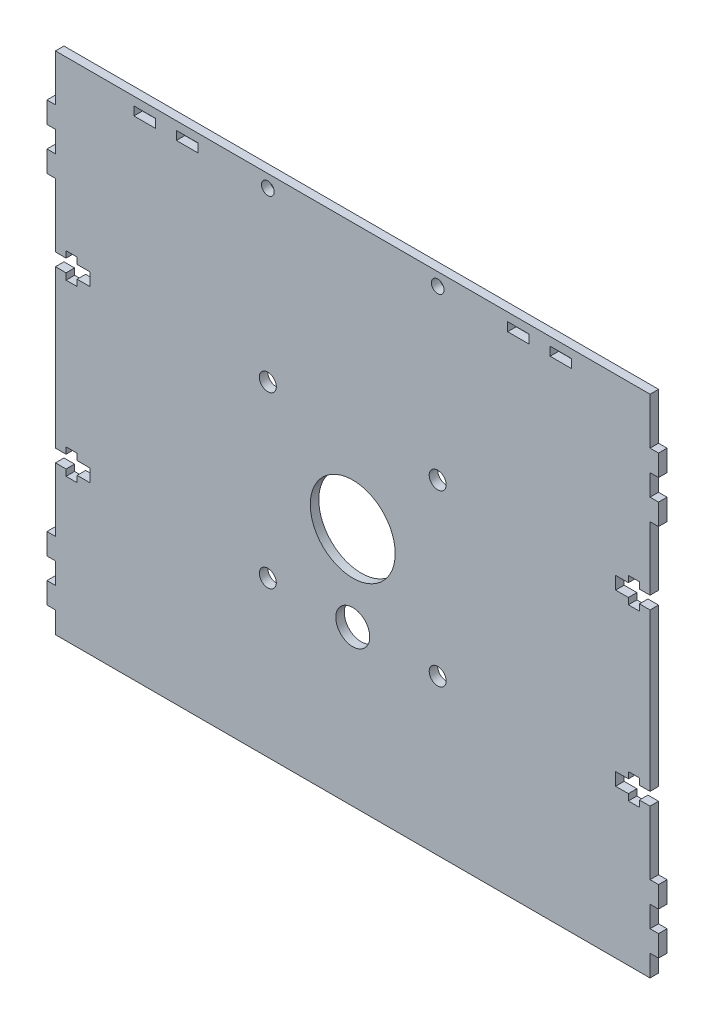
SolidWorks part; units mm, degrees
ref_plane "前视基准面" through (0, 0, 0) normal (0, 0, 1) x (1, 0, 0)
ref_plane "上视基准面" through (0, 0, 0) normal (0, 1, 0) x (1, 0, 0)
ref_plane "右视基准面" through (0, 0, 0) normal (1, 0, 0) x (0, 0, -1)
sketch "草图1" plane through (0, 0, 0) normal (0, 0, 1) x (1, 0, 0)
  line L50 (249.9534, 275.9629) -> (249.9534, 255.9629) construction
  line L53 (317.4534, 257.4629) -> (317.4534, 258.9629)
  line L54 (317.4534, 254.4629) -> (317.4534, 252.9629)
  line L55 (319.9534, 254.4629) -> (317.4534, 254.4629)
  line L56 (317.4534, 258.9629) -> (314.8534, 258.9629)
  line L57 (314.8534, 258.9629) -> (314.8534, 257.4629)
  line L58 (314.8534, 257.4629) -> (311.8534, 257.4629)
  line L59 (311.8534, 254.4629) -> (311.8534, 257.4629)
  line L60 (314.8534, 254.4629) -> (311.8534, 254.4629)
  line L61 (314.8534, 252.9629) -> (314.8534, 254.4629)
  line L62 (317.4534, 252.9629) -> (314.8534, 252.9629)
  line L63 (317.4534, 257.4629) -> (319.9534, 257.4629)
  line L68 (319.9534, 254.4629) -> (319.9534, 257.4629) construction
  line L69 (311.8534, 255.9629) -> (319.9534, 255.9629) construction
  line L73 (311.8534, 295.9629) -> (319.9534, 295.9629) construction
  line L75 (317.4534, 294.4629) -> (319.9534, 294.4629)
  line L76 (317.4534, 298.9629) -> (314.8534, 298.9629)
  line L77 (314.8534, 298.9629) -> (314.8534, 297.4629)
  line L78 (314.8534, 297.4629) -> (311.8534, 297.4629)
  line L79 (311.8534, 297.4629) -> (311.8534, 294.4629)
  line L80 (314.8534, 294.4629) -> (311.8534, 294.4629)
  line L81 (314.8534, 292.9629) -> (314.8534, 294.4629)
  line L82 (317.4534, 292.9629) -> (314.8534, 292.9629)
  line L83 (319.9534, 297.4629) -> (317.4534, 297.4629)
  line L84 (317.4534, 297.4629) -> (317.4534, 298.9629)
  line L85 (317.4534, 294.4629) -> (317.4534, 292.9629)
  line L111 (182.4534, 294.4629) -> (182.4534, 292.9629)
  line L112 (182.4534, 297.4629) -> (182.4534, 298.9629)
  line L113 (179.9534, 297.4629) -> (182.4534, 297.4629)
  line L114 (182.4534, 292.9629) -> (185.0534, 292.9629)
  line L115 (185.0534, 292.9629) -> (185.0534, 294.4629)
  line L116 (185.0534, 294.4629) -> (188.0534, 294.4629)
  line L117 (188.0534, 297.4629) -> (188.0534, 294.4629)
  line L118 (185.0534, 297.4629) -> (188.0534, 297.4629)
  line L119 (185.0534, 298.9629) -> (185.0534, 297.4629)
  line L120 (182.4534, 298.9629) -> (185.0534, 298.9629)
  line L121 (182.4534, 294.4629) -> (179.9534, 294.4629)
  line L122 (182.4534, 257.4629) -> (179.9534, 257.4629)
  line L123 (182.4534, 252.9629) -> (185.0534, 252.9629)
  line L124 (185.0534, 252.9629) -> (185.0534, 254.4629)
  line L125 (185.0534, 254.4629) -> (188.0534, 254.4629)
  line L126 (188.0534, 254.4629) -> (188.0534, 257.4629)
  line L127 (185.0534, 257.4629) -> (188.0534, 257.4629)
  line L128 (185.0534, 258.9629) -> (185.0534, 257.4629)
  line L129 (182.4534, 258.9629) -> (185.0534, 258.9629)
  line L130 (179.9534, 254.4629) -> (182.4534, 254.4629)
  line L131 (182.4534, 254.4629) -> (182.4534, 252.9629)
  line L132 (182.4534, 257.4629) -> (182.4534, 258.9629)
  line L133 (179.9534, 297.4629) -> (179.9534, 294.4629) construction
  line L134 (188.0534, 295.9629) -> (179.9534, 295.9629) construction
  line L135 (188.0534, 255.9629) -> (179.9534, 255.9629) construction
  line L163 (179.9534, 294.4629) -> (179.9534, 257.4629)
  line L172 (319.9534, 257.4629) -> (319.9534, 294.4629)
  line L188 (179.9534, 239.4629) -> (177.9534, 239.4629)
  line L189 (177.9534, 239.4629) -> (177.9534, 234.4629)
  line L190 (177.9534, 234.4629) -> (179.9534, 234.4629)
  line L191 (179.9534, 234.4629) -> (179.9534, 229.4629)
  line L192 (179.9534, 229.4629) -> (177.9534, 229.4629)
  line L193 (177.9534, 229.4629) -> (177.9534, 224.4629)
  line L194 (177.9534, 224.4629) -> (179.9534, 224.4629)
  line L196 (179.9534, 327.4629) -> (179.9534, 345.9629) construction
  line L197 (177.9534, 327.4629) -> (179.9534, 327.4629)
  line L198 (177.9534, 322.4629) -> (177.9534, 327.4629)
  line L199 (179.9534, 322.4629) -> (177.9534, 322.4629)
  line L200 (179.9534, 317.4629) -> (179.9534, 322.4629)
  line L201 (177.9534, 317.4629) -> (179.9534, 317.4629)
  line L202 (177.9534, 312.4629) -> (177.9534, 317.4629)
  line L203 (179.9534, 312.4629) -> (177.9534, 312.4629)
  line L224 (319.9534, 312.4629) -> (321.9534, 312.4629)
  line L225 (321.9534, 312.4629) -> (321.9534, 317.4629)
  line L226 (321.9534, 317.4629) -> (319.9534, 317.4629)
  line L227 (319.9534, 317.4629) -> (319.9534, 322.4629)
  line L228 (319.9534, 322.4629) -> (321.9534, 322.4629)
  line L229 (321.9534, 322.4629) -> (321.9534, 327.4629)
  line L230 (321.9534, 327.4629) -> (319.9534, 327.4629)
  line L231 (319.9534, 327.4629) -> (319.9534, 345.9629) construction
  line L233 (321.9534, 224.4629) -> (319.9534, 224.4629)
  line L234 (321.9534, 229.4629) -> (321.9534, 224.4629)
  line L235 (319.9534, 229.4629) -> (321.9534, 229.4629)
  line L236 (319.9534, 234.4629) -> (319.9534, 229.4629)
  line L237 (321.9534, 234.4629) -> (319.9534, 234.4629)
  line L238 (321.9534, 239.4629) -> (321.9534, 234.4629)
  line L239 (319.9534, 239.4629) -> (321.9534, 239.4629)
  line L261 (249.9534, 255.9629) -> (229.9534, 255.9629) construction
  line L262 (229.9534, 335.4629) -> (269.9534, 335.4629) construction
  line L263 (249.9534, 335.4629) -> (249.9534, 338.4629) construction
  line L268 (179.9534, 297.4629) -> (179.9534, 312.4629)
  line L271 (319.9534, 312.4629) -> (319.9534, 297.4629)
  line L272 (319.9534, 254.4629) -> (319.9534, 239.4629)
  line L275 (179.9534, 239.4629) -> (179.9534, 254.4629)
  line L279 (319.9534, 338.4629) -> (179.9534, 338.4629)
  line L280 (179.9534, 327.4629) -> (179.9534, 338.4629)
  line L285 (319.9534, 338.4629) -> (319.9534, 327.4629)
  line L286 (319.9534, 219.4131) -> (179.9534, 219.4131) construction
  line L287 (319.9534, 219.4131) -> (319.9534, 224.4629)
  line L288 (179.9534, 224.4629) -> (179.9534, 219.4131)
  line L289 (319.9534, 219.4131) -> (179.9534, 219.4131)
  line L309 (179.9534, 345.9629) -> (319.9534, 345.9629) construction
  line L310 (203.4784, 334.4379) -> (198.4284, 336.4879) construction
  line L311 (286.4284, 336.4879) -> (291.4784, 336.4879)
  line L312 (286.4284, 336.4879) -> (286.4284, 334.4379)
  line L313 (286.4284, 334.4379) -> (291.4784, 334.4379)
  line L314 (291.4784, 336.4879) -> (291.4784, 334.4379)
  line L315 (286.4284, 336.4879) -> (291.4784, 334.4379) construction
  line L316 (286.4284, 334.4379) -> (291.4784, 336.4879) construction
  line L317 (296.4284, 336.4879) -> (301.4784, 336.4879)
  line L318 (296.4284, 336.4879) -> (296.4284, 334.4379)
  line L319 (296.4284, 334.4379) -> (301.4784, 334.4379)
  line L320 (301.4784, 336.4879) -> (301.4784, 334.4379)
  line L321 (296.4284, 336.4879) -> (301.4784, 334.4379) construction
  line L322 (296.4284, 334.4379) -> (301.4784, 336.4879) construction
  line L323 (268.4534, 343.4629) -> (266.9534, 343.4629) [skipped]
  line L324 (271.4534, 343.4629) -> (272.9534, 343.4629) [skipped]
  line L325 (271.4534, 345.9629) -> (271.4534, 343.4629) [skipped]
  line L326 (266.9534, 343.4629) -> (266.9534, 340.8629) [skipped]
  line L327 (266.9534, 340.8629) -> (268.4534, 340.8629) [skipped]
  line L328 (268.4534, 340.8629) -> (268.4534, 337.8629) [skipped]
  line L329 (271.4534, 340.8629) -> (271.4534, 337.8629) [skipped]
  line L330 (272.9534, 340.8629) -> (271.4534, 340.8629) [skipped]
  line L331 (272.9534, 343.4629) -> (272.9534, 340.8629) [skipped]
  line L332 (268.4534, 343.4629) -> (268.4534, 345.9629) [skipped]
  line L333 (231.4534, 343.4629) -> (231.4534, 345.9629) [skipped]
  line L334 (226.9534, 343.4629) -> (226.9534, 340.8629) [skipped]
  line L335 (226.9534, 340.8629) -> (228.4534, 340.8629) [skipped]
  line L336 (228.4534, 340.8629) -> (228.4534, 337.8629) [skipped]
  line L337 (231.4534, 340.8629) -> (231.4534, 337.8629) [skipped]
  line L338 (232.9534, 340.8629) -> (231.4534, 340.8629) [skipped]
  line L339 (232.9534, 343.4629) -> (232.9534, 340.8629) [skipped]
  line L340 (228.4534, 345.9629) -> (228.4534, 343.4629) [skipped]
  line L341 (228.4534, 343.4629) -> (226.9534, 343.4629) [skipped]
  line L342 (231.4534, 343.4629) -> (232.9534, 343.4629) [skipped]
  line L343 (268.4534, 345.9629) -> (231.4534, 345.9629) [skipped]
  line L344 (213.4534, 345.9629) -> (213.4534, 347.9629) [skipped]
  line L345 (213.4534, 347.9629) -> (208.4534, 347.9629) [skipped]
  line L346 (208.4534, 347.9629) -> (208.4534, 345.9629) [skipped]
  line L347 (208.4534, 345.9629) -> (203.4534, 345.9629) [skipped]
  line L348 (203.4534, 345.9629) -> (203.4534, 347.9629) [skipped]
  line L349 (203.4534, 347.9629) -> (198.4534, 347.9629) [skipped]
  line L350 (198.4534, 347.9629) -> (198.4534, 345.9629) [skipped]
  line L352 (301.4534, 345.9629) -> (319.9534, 345.9629) [skipped]
  line L353 (301.4534, 347.9629) -> (301.4534, 345.9629) [skipped]
  line L354 (296.4534, 347.9629) -> (301.4534, 347.9629) [skipped]
  line L355 (296.4534, 345.9629) -> (296.4534, 347.9629) [skipped]
  line L356 (291.4534, 345.9629) -> (296.4534, 345.9629) [skipped]
  line L357 (291.4534, 347.9629) -> (291.4534, 345.9629) [skipped]
  line L358 (286.4534, 347.9629) -> (291.4534, 347.9629) [skipped]
  line L359 (286.4534, 345.9629) -> (286.4534, 347.9629) [skipped]
  line L360 (271.4534, 345.9629) -> (268.4534, 345.9629) construction
  line L361 (269.9534, 337.8629) -> (269.9534, 345.9629) construction
  line L362 (229.9534, 337.8629) -> (229.9534, 345.9629) construction
  line L363 (271.4534, 337.8629) -> (268.4534, 337.8629) [skipped]
  line L364 (228.4534, 337.8629) -> (231.4534, 337.8629) [skipped]
  line L365 (203.4784, 336.4879) -> (198.4284, 334.4379) construction
  line L366 (213.4784, 334.4379) -> (208.4284, 336.4879) construction
  line L367 (213.4784, 336.4879) -> (208.4284, 334.4379) construction
  line L368 (198.4284, 336.4879) -> (198.4284, 334.4379)
  line L369 (203.4784, 334.4379) -> (198.4284, 334.4379)
  line L370 (203.4784, 336.4879) -> (203.4784, 334.4379)
  line L371 (203.4784, 336.4879) -> (198.4284, 336.4879)
  line L372 (208.4284, 336.4879) -> (208.4284, 334.4379)
  line L373 (213.4784, 334.4379) -> (208.4284, 334.4379)
  line L374 (213.4784, 336.4879) -> (213.4784, 334.4379)
  line L375 (213.4784, 336.4879) -> (208.4284, 336.4879)
  line L376 (231.4534, 208.4629) -> (232.9534, 208.4629) [skipped]
  line L377 (228.4534, 208.4629) -> (226.9534, 208.4629) [skipped]
  line L378 (228.4534, 205.9629) -> (228.4534, 208.4629) [skipped]
  line L379 (232.9534, 208.4629) -> (232.9534, 211.0629) [skipped]
  line L380 (232.9534, 211.0629) -> (231.4534, 211.0629) [skipped]
  line L381 (231.4534, 211.0629) -> (231.4534, 214.0629) [skipped]
  line L382 (228.4534, 214.0629) -> (231.4534, 214.0629) [skipped]
  line L383 (228.4534, 211.0629) -> (228.4534, 214.0629) [skipped]
  line L384 (226.9534, 211.0629) -> (228.4534, 211.0629) [skipped]
  line L385 (226.9534, 208.4629) -> (226.9534, 211.0629) [skipped]
  line L386 (231.4534, 208.4629) -> (231.4534, 205.9629) [skipped]
  line L387 (268.4534, 208.4629) -> (268.4534, 205.9629) [skipped]
  line L388 (272.9534, 208.4629) -> (272.9534, 211.0629) [skipped]
  line L389 (272.9534, 211.0629) -> (271.4534, 211.0629) [skipped]
  line L390 (271.4534, 211.0629) -> (271.4534, 214.0629) [skipped]
  line L391 (271.4534, 214.0629) -> (268.4534, 214.0629) [skipped]
  line L392 (268.4534, 211.0629) -> (268.4534, 214.0629) [skipped]
  line L393 (266.9534, 211.0629) -> (268.4534, 211.0629) [skipped]
  line L394 (266.9534, 208.4629) -> (266.9534, 211.0629) [skipped]
  line L395 (271.4534, 205.9629) -> (271.4534, 208.4629) [skipped]
  line L396 (271.4534, 208.4629) -> (272.9534, 208.4629) [skipped]
  line L397 (268.4534, 208.4629) -> (266.9534, 208.4629) [skipped]
  line L398 (231.4534, 205.9629) -> (268.4534, 205.9629) [skipped]
  line L399 (286.4534, 205.9629) -> (286.4534, 203.9629) [skipped]
  line L400 (286.4534, 203.9629) -> (291.4534, 203.9629) [skipped]
  line L401 (291.4534, 203.9629) -> (291.4534, 205.9629) [skipped]
  line L402 (291.4534, 205.9629) -> (296.4534, 205.9629) [skipped]
  line L403 (296.4534, 205.9629) -> (296.4534, 203.9629) [skipped]
  line L404 (296.4534, 203.9629) -> (301.4534, 203.9629) [skipped]
  line L405 (198.4534, 205.9629) -> (179.9534, 205.9629) [skipped]
  line L406 (198.4534, 203.9629) -> (198.4534, 205.9629) [skipped]
  line L407 (203.4534, 203.9629) -> (198.4534, 203.9629) [skipped]
  line L408 (203.4534, 205.9629) -> (203.4534, 203.9629) [skipped]
  line L409 (208.4534, 205.9629) -> (203.4534, 205.9629) [skipped]
  line L410 (208.4534, 203.9629) -> (208.4534, 205.9629) [skipped]
  line L411 (213.4534, 203.9629) -> (208.4534, 203.9629) [skipped]
  line L412 (213.4534, 205.9629) -> (213.4534, 203.9629) [skipped]
  line L413 (228.4534, 205.9629) -> (231.4534, 205.9629) construction
  line L414 (229.9534, 214.0629) -> (229.9534, 205.9629) construction
  line L415 (269.9534, 214.0629) -> (269.9534, 205.9629) construction
  line L416 (319.9534, 224.4629) -> (319.9534, 205.9629) [skipped]
  line L417 (301.4534, 203.9629) -> (301.4534, 205.9629) [skipped]
  circle A14 centre (249.9534, 275.9629) radius 10
  circle A24 centre (249.9534, 255.9629) radius 4
  circle A27 centre (229.9534, 335.4629) radius 1.5
  circle A28 centre (269.9534, 335.4629) radius 1.5
  circle A29 centre (229.9534, 255.9629) radius 2
  circle A30 centre (229.9534, 295.9629) radius 2
  circle A31 centre (269.9534, 295.9629) radius 2
  circle A32 centre (269.9534, 255.9629) radius 2
  circle A33 centre (249.9534, 255.9629) radius 31.5 construction
  point P107 (210.9534, 335.4629)
  point P232 (288.9534, 335.4629)
  dimension "D1" = 140
  dimension "D5" = 4
  dimension "D4" = 4
extrude "凸台-拉伸1" add sketch "草图1" along normal blind 2
sketch "草图2" plane through (179.9534, 0, 0) normal (-1, 0, 0) x (0, 0, 1)
  line L0 (1, 294.4629) -> (1, 297.4629) construction
  line L1 (2, 294.4629) -> (0, 294.4629) construction
  line L2 (2, 297.4629) -> (0, 297.4629) construction
  line L3 (1, 295.9629) -> (1, 312.4629) construction
  line L4 (2, 312.4629) -> (0, 312.4629) construction
  circle A0 centre (1, 295.9629) radius 1.5
sketch "草图4" plane through (319.9534, 0, 0) normal (1, 0, 0) x (0, 0, -1)
  line L0 (-1, 257.4629) -> (-1, 254.4629) construction
  line L1 (-2, 257.4629) -> (0, 257.4629) construction
  line L2 (-2, 254.4629) -> (0, 254.4629) construction
  circle A0 centre (-1, 255.9629) radius 1.5
sketch "草图6" plane through (0, 0, 2) normal (0, 0, 1) x (1, 0, 0)
  line L0 (317.9092, 345.9629) -> (317.9092, 336.4629)
  line L2 (317.9092, 336.4629) -> (319.9534, 336.4629)
  line L3 (319.9534, 336.4629) -> (319.9534, 345.9629)
  line L4 (319.9534, 345.9629) -> (317.9092, 345.9629)
